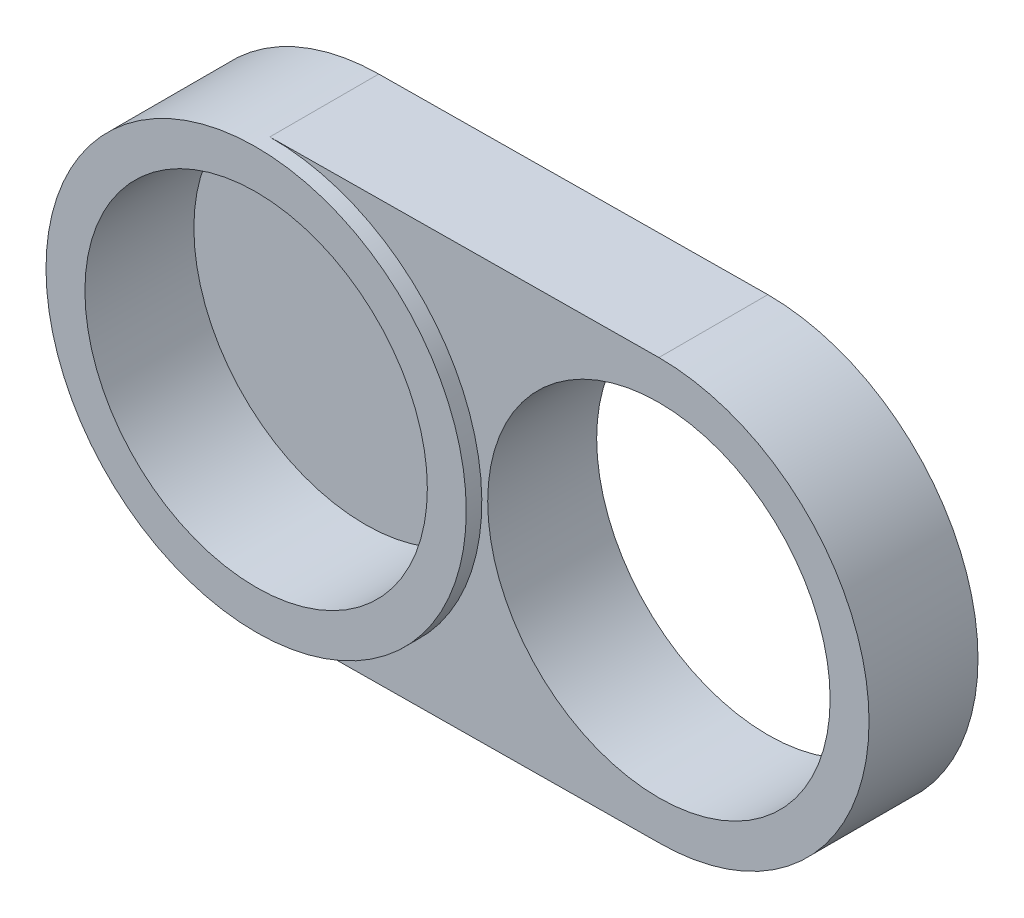
SolidWorks part; units mm, degrees
ref_plane "Front Plane" through (0, 0, 0) normal (0, 0, 1) x (1, 0, 0)
ref_plane "Top Plane" through (0, 0, 0) normal (0, 1, 0) x (1, 0, 0)
ref_plane "Right Plane" through (0, 0, 0) normal (1, 0, 0) x (0, 0, -1)
sketch "Sketch1" plane through (0, 0, 0) normal (0, 0, 1) x (1, 0, 0)
  line L0 (0, 13.5) -> (-25, 13.2734)
  line L1 (-24.8776, -13.7261) -> (0, -13.5)
  circle A0 centre (0, 0) radius 11
  arc A1 (0, -13.5) -> (-0.2447, 13.4978) centre (0, 0) ccw
  arc A2 (-25, 13.2734) -> (-24.6323, -13.7238) centre (-24.8776, -0.2261) ccw
  circle A3 centre (-24.8776, -0.2261) radius 11
  dimension "D1" = 22
  dimension "D2" = 27
  dimension "D3" = 25
extrude "Boss-Extrude1" add sketch "Sketch1" along normal blind 7 contours L0 A2 L1 A1 A3 A0
sketch "Sketch2" plane through (0, 0, 0) normal (0, 0, -1) x (-1, 0, 0)
  circle A0 centre (24.8776, -0.2261) radius 11 construction
  circle A1 centre (24.8776, -0.2261) radius 11
extrude "Boss-Extrude2" add sketch "Sketch2" against normal blind 1
sketch "Sketch3" plane through (0, 0, 7) normal (0, 0, 1) x (1, 0, 0)
  circle A0 centre (-24.8776, -0.2261) radius 11
  circle A1 centre (-24.8776, -0.2261) radius 13.5
extrude "Boss-Extrude3" add sketch "Sketch3" along normal blind 1
